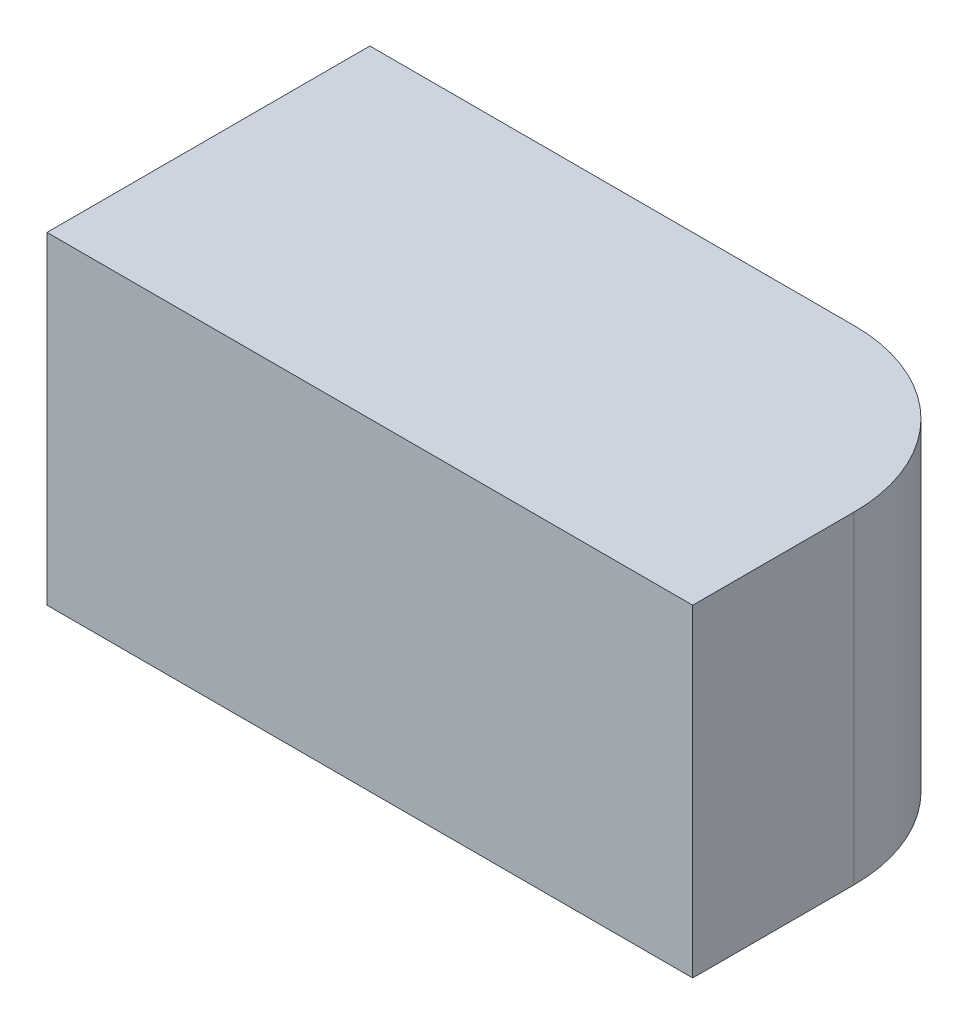
SolidWorks part; units mm, degrees
ref_plane "Přední rovina" through (0, 0, 0) normal (0, 0, 1) x (1, 0, 0)
ref_plane "Horní rovina" through (0, 0, 0) normal (0, 1, 0) x (1, 0, 0)
ref_plane "Pravá rovina" through (0, 0, 0) normal (1, 0, 0) x (0, 0, -1)
sketch "Sketch1" plane through (0, 0, 0) normal (0, 1, 0) x (1, 0, 0)
  line L0 (0, 0) -> (30, 0)
  line L1 (-10, -20) -> (30, -20)
  line L2 (-10, -20) -> (-10, -10)
  line L4 (30, -20) -> (30, 0)
  arc A0 (-10, -10) -> (0, 0) centre (0, -10) cw
  dimension "D1" = 10
  dimension "D2" = 40
  dimension "D3" = 20
extrude "Boss-Extrude1" add sketch "Sketch1" along normal blind 20
mirror "Mirror2" about plane through (-10, 20, 20) normal (1, 0, 0) of bodies 101
delete or keep bodies "Body-Delete/Keep 2" type delete bodies bodies 101
equation "\"R\"= 10'Radius"
equation "\"H\"= 20'Extrude height"
equation "\"D1@Boss-Extrude1\"=\"H\""
equation "\"D2@Sketch1\"=\"R\"*4"
equation "\"D3@Sketch1\"=\"R\"*2mm"
equation "\"D1@Sketch1\"=\"R\""
